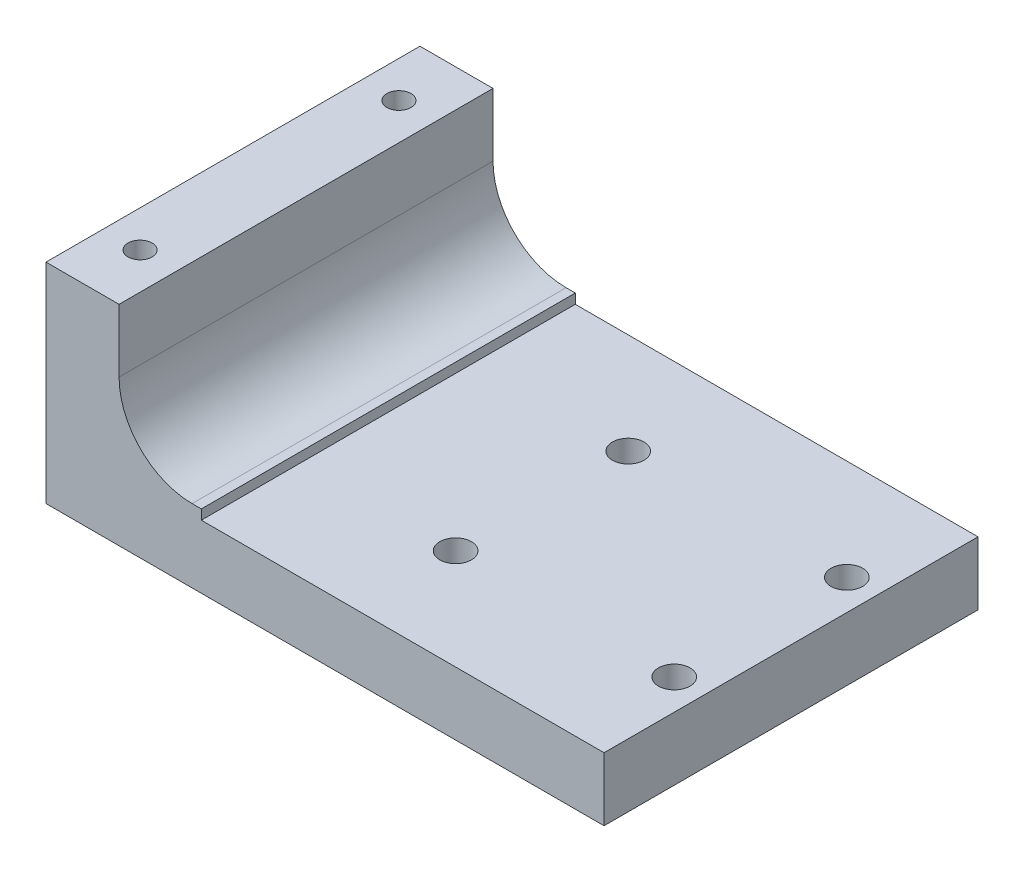
SolidWorks part; units mm, degrees
material "6061-T6 ALUMINUM"
ref_plane "Front/Back" through (0, 0, 0) normal (0, 0, 1) x (1, 0, 0)
ref_plane "Top/Bottom" through (0, 0, 0) normal (0, 1, 0) x (1, 0, 0)
ref_plane "Right/Left" through (0, 0, 0) normal (1, 0, 0) x (0, 0, -1)
sketch "Sketch1" plane through (0, 0, 0) normal (0, 0, 1) x (1, 0, 0)
  line L0 (0, 0) -> (97, 0)
  line L1 (0, 0) -> (0, 36.35)
  line L2 (0, 36.35) -> (12.7, 36.35)
  line L3 (12.7, 36.35) -> (12.7, 25.4)
  line L4 (25.4, 12.7) -> (97, 12.7)
  line L5 (97, 12.7) -> (97, 0)
  arc A0 (12.7, 25.4) -> (25.4, 12.7) centre (25.4, 25.4) ccw
  dimension "D1" = 12.7
  dimension "D2" = 12.7
  dimension "D3" = 36.35
  dimension "D4" = 97
extrude "Extrude1" add sketch "Sketch1" along normal mid plane 65
sketch "Sketch2" plane through (0, 0, -32.5) normal (0, 0, -1) x (-1, 0, 0)
  line L0 (0, 0) -> (-97, 0) construction
  line L1 (-97, 12.7) -> (-27, 12.7)
  line L2 (-97, 12.7) -> (-97, 11)
  line L3 (-97, 11) -> (-27, 11)
  line L4 (-27, 12.7) -> (-27, 11)
  dimension "D1" = 70
  dimension "D2" = 11
extrude "Cut-Extrude1" cut sketch "Sketch2" against normal through all
hole_wizard "M5 Clearance Hole1" positions "Sketch4" profile "Sketch3" hole size "M5" standard "_*ATS Preferred Ansi METRIC" end condition through all
sketch "Sketch4" plane through (0, 0, 0) normal (0, -1, 0) x (1, 0, 0)
  point P0 (53.7, 15)
  point P1 (91.7, 15)
  point P4 (91.7, -15)
  point P7 (53.7, -15)
sketch "Sketch3" plane through (53.7, 0, 15) normal (1, 0, 0) x (0, 0, -1)
  line L0 (0, 0) -> (0, 36.35)
  line L1 (0, 36.35) -> (2.75, 36.35)
  line L2 (2.75, 36.35) -> (2.75, 0)
  line L5 (2.75, 0) -> (0, 0)
  line L11 (0, -6.35) -> (0, 107.95) construction
  dimension "Thru Hole Dia." = 5.5
  dimension "Thru Hole Depth" = 36.35
hole_wizard "M5x0.8 Tapped Hole1" positions "Sketch6" profile "Sketch5" tap size "M5x0.8" standard "_*ATS Preferred Ansi METRIC"
sketch "Sketch6" plane through (0, 36.35, 0) normal (0, 1, 0) x (-1, 0, 0)
  line L0 (0, 0) -> (-12.7, 0) construction
  line L1 (-12.7, 32.5) -> (-12.7, -32.5) construction
  line L4 (-6.35, 0) -> (-6.35, 14.0998) construction
  point P0 (-6.35, 22.5)
  point P1 (-6.35, -22.5)
  dimension "D1" = 45
sketch "Sketch5" plane through (6.35, 36.35, 22.5) normal (1, 0, 0) x (0, 0, 1)
  line L0 (0, 0) -> (0, 20.3118)
  line L1 (0, 20.3118) -> (2.1, 19.05)
  line L2 (2.1, 19.05) -> (2.1, 0)
  line L5 (2.1, 0) -> (0, 0)
  line L10 (0, 20.3118) -> (-2.1, 19.05) construction
  line L11 (0, -6.35) -> (0, 107.95) construction
  dimension "Tap Drill Dia." = 4.2
  dimension "Tap Drill Depth" = 19.05
  dimension "Drill Angle" = 118
cosmetic thread "Hole Thread1" parameters "D1"=10, "D2"=5
cosmetic thread "Hole Thread2" parameters "D1"=10, "D2"=5
